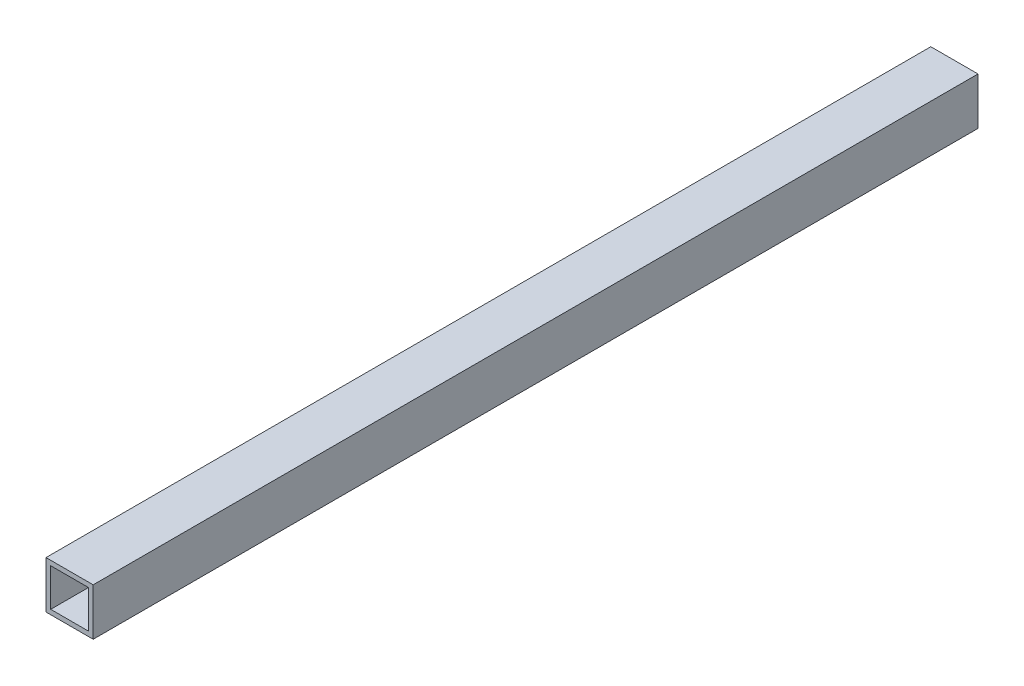
SolidWorks part; units mm, degrees
material "Д16Т ГОСТ 4784-74"
ref_plane "Спереди" through (0, 0, 0) normal (0, 0, 1) x (1, 0, 0)
ref_plane "Сверху" through (0, 0, 0) normal (0, 1, 0) x (1, 0, 0)
ref_plane "Справа" through (0, 0, 0) normal (1, 0, 0) x (0, 0, -1)
sketch "Эскиз1" plane through (0, 0, 0) normal (0, 0, 1) x (1, 0, 0)
  line L1 (0, 0) -> (40, 0)
  line L2 (0, 0) -> (0, 40)
  line L3 (0, 40) -> (40, 40)
  line L4 (40, 0) -> (40, 40)
  dimension "D1" = 40
  dimension "D2" = 40
extrude "Вытянуть-Тонкостенный1" add sketch "Эскиз1" along normal blind 750 thin thin type one direction reverse wall 4
